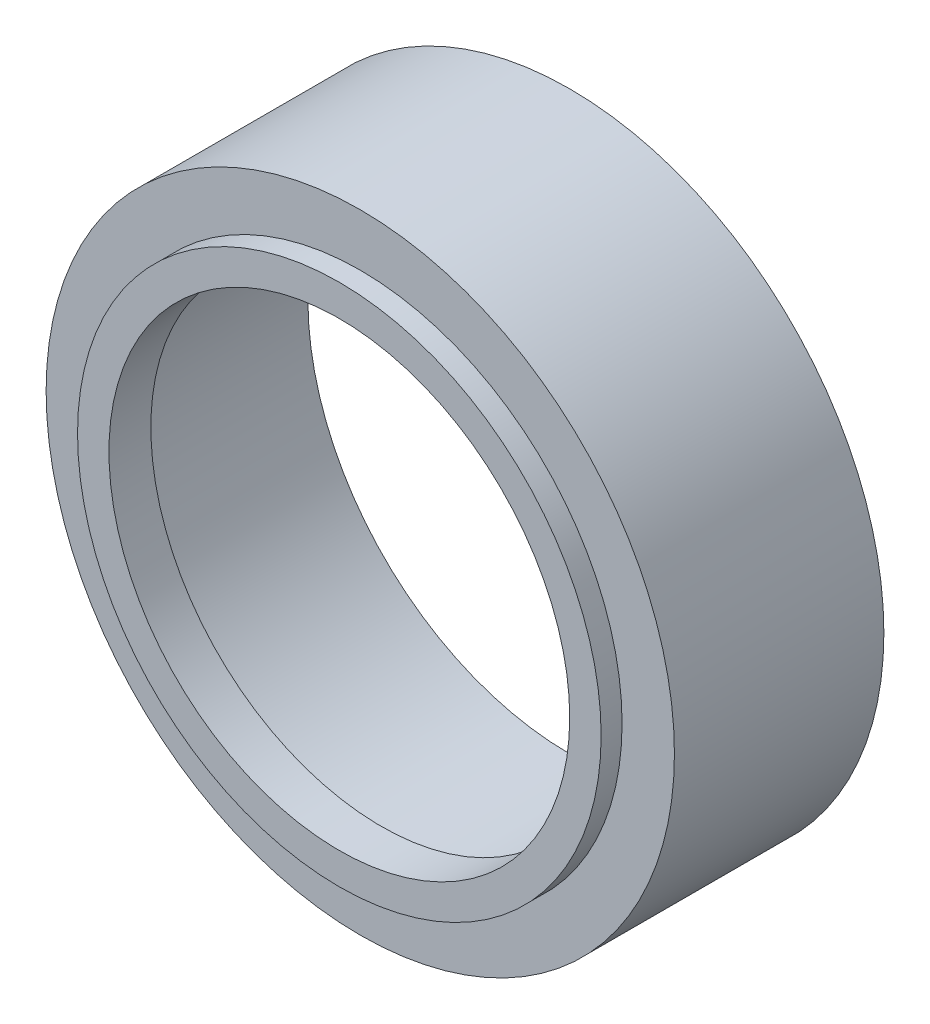
SolidWorks part; units mm, degrees
ref_plane "Plan de face" through (0, 0, 0) normal (0, 0, 1) x (1, 0, 0)
ref_plane "Plan de dessus" through (0, 0, 0) normal (0, 1, 0) x (1, 0, 0)
ref_plane "Plan de droite" through (0, 0, 0) normal (1, 0, 0) x (0, 0, -1)
sketch "Esquisse1" plane through (0, 0, 0) normal (0, 0, 1) x (1, 0, 0)
  circle A0 centre (0, 0) radius 15
extrude "Boss.-Extru.1" add sketch "Esquisse1" along normal blind 10
sketch "Esquisse2" plane through (0, 0, 10) normal (0, 0, 1) x (1, 0, 0)
  circle A0 centre (0, 0) radius 12.5
extrude "Boss.-Extru.2" add sketch "Esquisse2" along normal blind 1
sketch "Esquisse3" plane through (0, 0, 11) normal (0, 0, 1) x (1, 0, 0)
  circle A0 centre (0, 0) radius 11
extrude "Enlèv. mat.-Extru.1" cut sketch "Esquisse3" against normal blind 2
sketch "Esquisse4" plane through (0, 0, 0) normal (0, 0, -1) x (-1, 0, 0)
  circle A0 centre (0, 0) radius 12.5
extrude "Enlèv. mat.-Extru.2" cut sketch "Esquisse4" against normal blind 9
